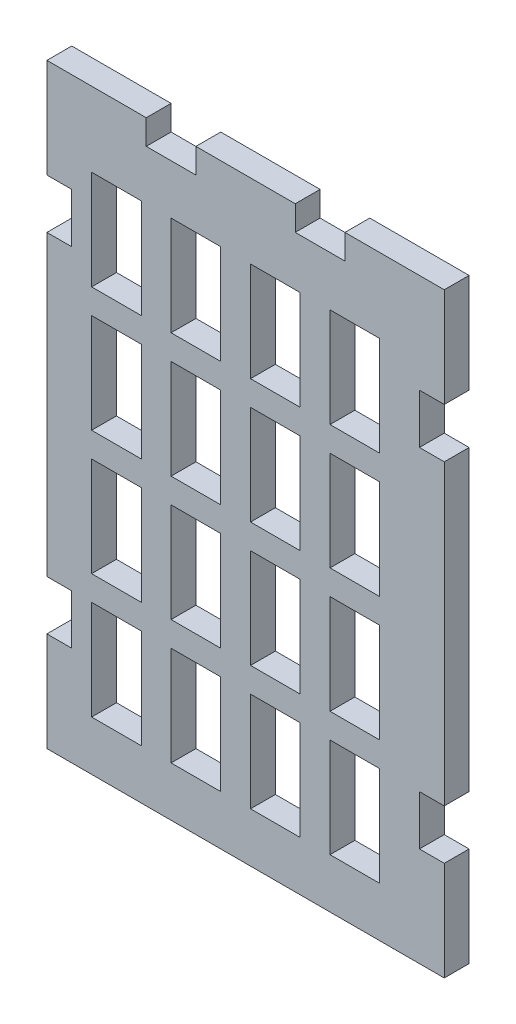
SolidWorks part; units mm, degrees
ref_plane "Front Plane" through (0, 0, 0) normal (0, 0, 1) x (1, 0, 0)
ref_plane "Top Plane" through (0, 0, 0) normal (0, 1, 0) x (1, 0, 0)
ref_plane "Right Plane" through (0, 0, 0) normal (1, 0, 0) x (0, 0, -1)
sketch "Sketch1" plane through (0, 0, 0) normal (0, 0, 1) x (1, 0, 0)
  line L0 (12.7, -76.2) -> (38.1, -76.2)
  line L1 (0, 0) -> (50.8, 0)
  line L2 (0, 0) -> (0, -76.2)
  line L3 (0, -76.2) -> (12.7, -76.2)
  line L4 (50.8, 0) -> (50.8, -76.2)
  line L5 (12.7, 0) -> (19.05, 0)
  line L6 (12.7, 0) -> (12.7, -3.175)
  line L7 (12.7, -3.175) -> (19.05, -3.175)
  line L8 (19.05, 0) -> (19.05, -3.175)
  line L9 (31.75, 0) -> (38.1, 0)
  line L10 (31.75, 0) -> (31.75, -3.175)
  line L11 (31.75, -3.175) -> (38.1, -3.175)
  line L12 (38.1, 0) -> (38.1, -3.175)
  line L13 (50.8, -12.7) -> (47.625, -12.7)
  line L14 (50.8, -12.7) -> (50.8, -19.05)
  line L15 (50.8, -19.05) -> (47.625, -19.05)
  line L16 (47.625, -12.7) -> (47.625, -19.05)
  line L17 (50.8, -57.15) -> (47.625, -57.15)
  line L18 (50.8, -57.15) -> (50.8, -63.5)
  line L19 (50.8, -63.5) -> (47.625, -63.5)
  line L20 (47.625, -57.15) -> (47.625, -63.5)
  line L25 (38.1, -76.2) -> (50.8, -76.2)
  line L29 (0, -63.5) -> (3.175, -63.5)
  line L30 (0, -63.5) -> (0, -57.15)
  line L31 (0, -57.15) -> (3.175, -57.15)
  line L32 (3.175, -63.5) -> (3.175, -57.15)
  line L33 (0, -19.05) -> (3.175, -19.05)
  line L34 (0, -19.05) -> (0, -12.7)
  line L35 (0, -12.7) -> (3.175, -12.7)
  line L36 (3.175, -19.05) -> (3.175, -12.7)
  dimension "D1" = 50.8
  dimension "D2" = 76.2
  dimension "D3" = 12.7
  dimension "D4" = 6.35
  dimension "D5" = 3.175
  dimension "D6" = 6.35
  dimension "D7" = 3.175
  dimension "D8" = 12.7
  dimension "D9" = 12.7
  dimension "D10" = 6.35
  dimension "D11" = 3.175
  dimension "D12" = 3.175
  dimension "D13" = 6.35
  dimension "D14" = 12.7
  dimension "D21" = 3.175
  dimension "D22" = 6.35
  dimension "D23" = 12.7
  dimension "D24" = 12.7
  dimension "D25" = 6.35
  dimension "D26" = 3.175
extrude "Boss-Extrude1" add sketch "Sketch1" along normal blind 3.175
sketch "Sketch2" plane through (0, 0, 3.175) normal (0, 0, 1) x (1, 0, 0)
  line L0 (12.7, -3.175) -> (19.05, -3.175) construction
  line L1 (3.175, -19.05) -> (3.175, -12.7) construction
  line L7 (5.715, -9.525) -> (12.065, -9.525)
  line L8 (5.715, -9.525) -> (5.715, -22.225)
  line L9 (5.715, -22.225) -> (12.065, -22.225)
  line L10 (12.065, -9.525) -> (12.065, -22.225)
  line L11 (5.715, -9.525) -> (12.065, -22.225) construction
  line L12 (5.715, -22.225) -> (12.065, -9.525) construction
  point P5 (8.89, -15.875)
  dimension "D1" = 6.35
  dimension "D2" = 12.7
  dimension "D3" = 6.35
  dimension "D4" = 2.54
extrude "Cut-Extrude1" cut sketch "Sketch2" against normal blind 5.08
pattern_linear "LPattern1" count 4 spacing 10.16 along (1, 0, 0) count 4 spacing 15.875 along (0, -1, 0) of "Cut-Extrude1"
